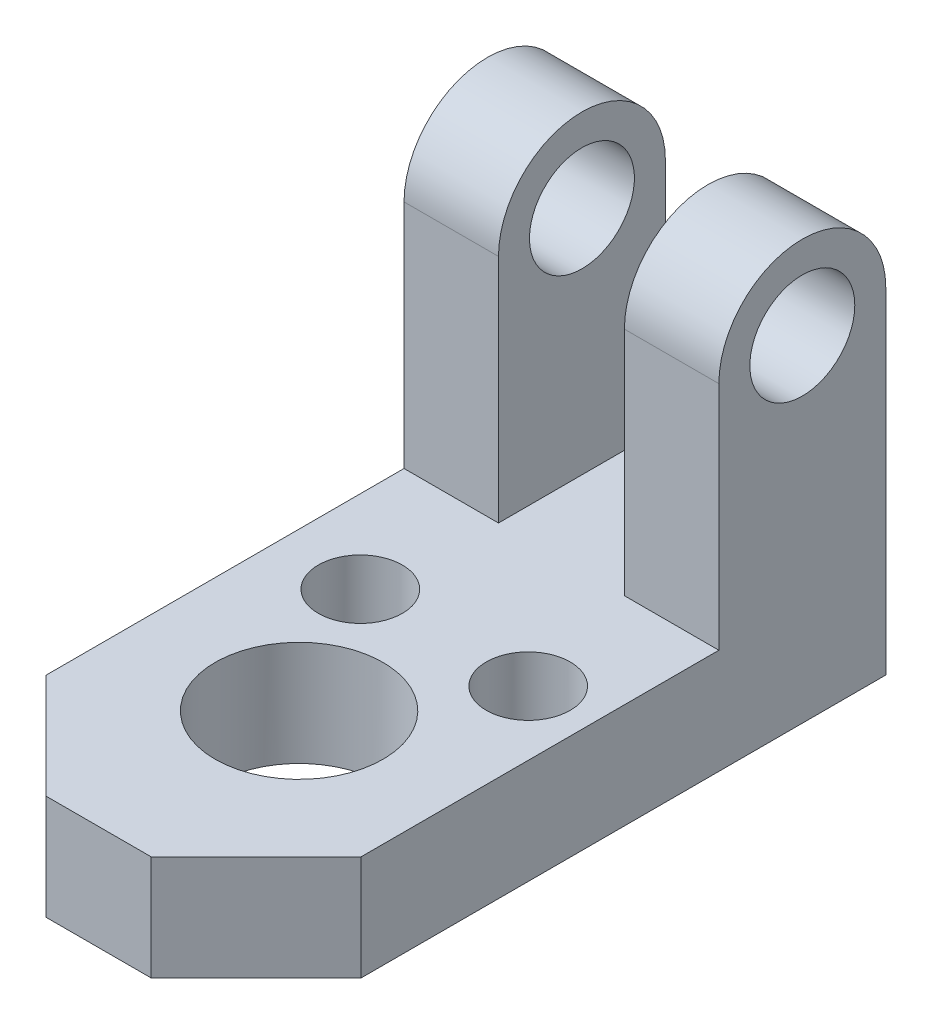
SolidWorks part; units mm, degrees
ref_plane "Front Plane" through (0, 0, 0) normal (0, 0, 1) x (1, 0, 0)
ref_plane "Top Plane" through (0, 0, 0) normal (0, 1, 0) x (1, 0, 0)
ref_plane "Right Plane" through (0, 0, 0) normal (1, 0, 0) x (0, 0, -1)
sketch "Sketch2" plane through (0, 0, 0) normal (0, 1, 0) x (1, 0, 0)
  line L0 (-16.7098, 47.2927) -> (13.2902, 47.2927)
  line L1 (13.2902, 47.2927) -> (13.2902, -12.7073)
  line L2 (13.2902, -12.7073) -> (-16.7098, -12.7073)
  line L3 (-16.7098, -12.7073) -> (-16.7098, 47.2927)
  dimension "D1" = 30
  dimension "D2" = 60
extrude "Boss-Extrude1" add sketch "Sketch2" along normal blind 10
chamfer "Chamfer1" distance 10 angle 45 1 edges at (-16.7098, 5, 12.7073)
chamfer "Chamfer2" distance 10 angle 45 1 edges at (13.2902, 5, 12.7073)
sketch "Sketch3" plane through (13.2902, 0, 0) normal (1, 0, 0) x (0, 0, -1)
  line L0 (47.2927, 10) -> (47.2927, 32)
  line L1 (47.2927, 32) -> (31.388, 32)
  line L2 (31.388, 32) -> (31.388, 10)
  line L3 (-2.7073, 10) -> (47.2927, 10) construction
  line L4 (31.388, 10) -> (47.2927, 10)
  dimension "D1" = 22
extrude "Boss-Extrude2" add sketch "Sketch3" against normal blind 9
sketch "Sketch5" plane through (0, 10, 0) normal (0, 1, 0) x (1, 0, 0)
  line L0 (-9.7098, 6.388) -> (6.2902, 6.388) construction
  line L2 (-16.7098, 6.388) -> (13.2902, 6.388) construction
  line L3 (-16.7098, 47.2927) -> (-16.7098, -2.7073) construction
  line L4 (13.2902, -2.7073) -> (13.2902, 31.388) construction
  line L5 (4.2902, 31.388) -> (13.2902, 31.388) construction
  circle A0 centre (-1.7098, 6.388) radius 8
  dimension "D1" = 16
  dimension "D2" = 25
extrude "Cut-Extrude4" cut sketch "Sketch5" against normal up to next
sketch "Sketch6" plane through (13.2902, 0, 0) normal (1, 0, 0) x (0, 0, -1)
  line L0 (47.2927, 32) -> (31.388, 32) construction
  circle A0 centre (39.3404, 32) radius 7.9524
extrude "Boss-Extrude3" add sketch "Sketch6" against normal blind 9
sketch "Sketch8" plane through (13.2902, 0, 0) normal (1, 0, 0) x (0, 0, -1)
  circle A0 centre (39.3404, 32) radius 5
  dimension "D1" = 10
extrude "Cut-Extrude5" cut sketch "Sketch8" against normal up to next
ref_plane "Plane17" through (-1.7098, 0, 0) normal (-1, 0, 0) x (0, 0, 1)
mirror "Mirror6" about plane through (-1.7098, 0, 0) normal (-1, 0, 0) of "Cut-Extrude5", "Boss-Extrude3", "Boss-Extrude2"
sketch "Sketch9" plane through (0, 10, 0) normal (0, 1, 0) x (1, 0, 0)
  circle A0 centre (-8.8316, 19.3436) radius 4
  circle A1 centre (7.1684, 19.3436) radius 4
  dimension "D1" = 8
  dimension "D2" = 8
  dimension "D3" = 16
extrude "Cut-Extrude6" cut sketch "Sketch9" against normal up to next
